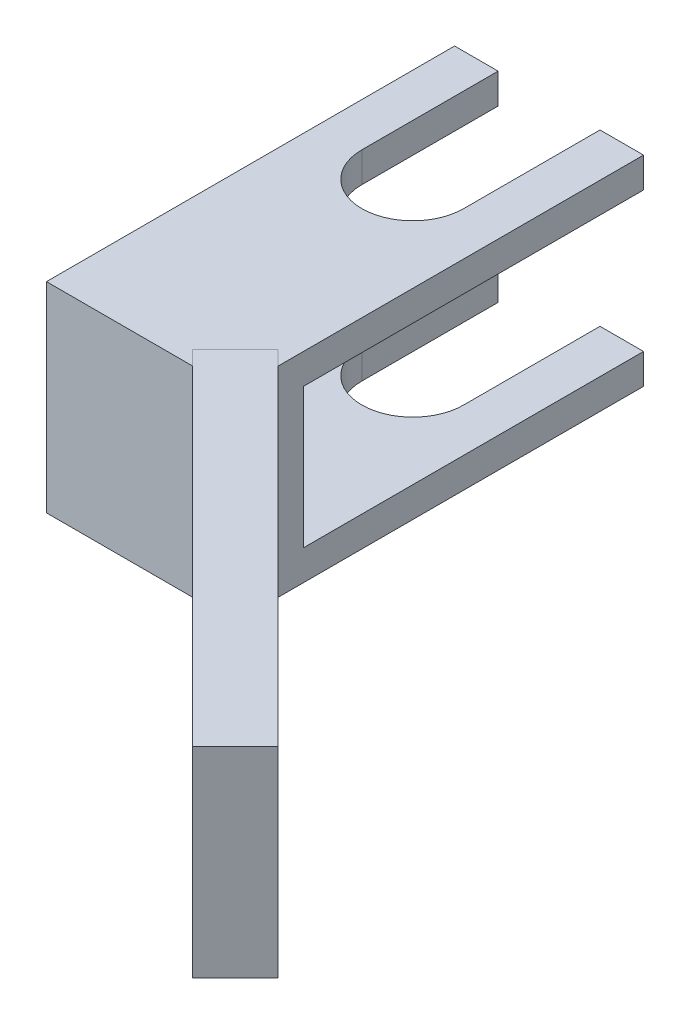
SolidWorks part; units mm, degrees
ref_plane "Front Plane" through (0, 0, 0) normal (0, 0, 1) x (1, 0, 0)
ref_plane "Top Plane" through (0, 0, 0) normal (0, 1, 0) x (1, 0, 0)
ref_plane "Right Plane" through (0, 0, 0) normal (1, 0, 0) x (0, 0, -1)
sketch "Sketch1" plane through (0, 0, 0) normal (0, 1, 0) x (1, 0, 0)
  line L1 (0, 0) -> (50, 0)
  line L2 (0, 0) -> (0, 100)
  line L3 (0, 100) -> (50, 100)
  line L4 (50, 0) -> (50, 100)
  dimension "D1" = 50
  dimension "D2" = 100
extrude "Boss-Extrude1" add sketch "Sketch1" along normal blind 8
sketch "Sketch2" plane through (0, 8, 0) normal (0, 1, 0) x (1, 0, 0)
  line L0 (24.9969, 63.9389) -> (25, 100) construction
  line L1 (50, 100) -> (0, 100) construction
  line L2 (11.5173, 63.94) -> (11.5204, 100.0012)
  line L3 (38.4764, 63.9377) -> (38.4796, 99.9988)
  arc A0 (11.5173, 63.94) -> (38.4764, 63.9377) centre (24.9969, 63.9389) ccw
  arc A1 (38.4796, 99.9988) -> (11.5204, 100.0012) centre (25, 100) ccw
  point P4 (24.9984, 81.9694)
  point P9 (24.9969, 63.9389)
extrude "Cut-Extrude1" cut sketch "Sketch2" against normal blind 8
pattern_linear "LPattern1" count 2 spacing 45 along (0, 1, 0) of "Boss-Extrude1"
sketch "Sketch3" plane through (0, 0, 0) normal (0, 0, 1) x (1, 0, 0)
  line L1 (0, 0) -> (50, 0)
  line L2 (0, 0) -> (0, 53)
  line L3 (0, 53) -> (50, 53)
  line L4 (50, 0) -> (50, 53)
extrude "Boss-Extrude2" add sketch "Sketch3" along normal blind 8 and the other way blind 10
ref_plane "Angled Plane" through (21, 0, -21) normal (0.7071, 0, -0.7071) x (-0.7071, 0, -0.7071)
sketch "Sketch4" plane through (21, 0, -21) normal (0.7071, 0, -0.7071) x (-0.7071, 0, -0.7071)
  line L1 (-27.701, 0) -> (-156.3964, 0)
  line L2 (-27.701, 0) -> (-27.701, 53)
  line L3 (-27.701, 53) -> (-156.3964, 53)
  line L4 (-156.3964, 0) -> (-156.3964, 53)
  point P5 (0, 0)
  point P6 (0, 0)
  point P7 (0, 0)
  point P8 (0, 0)
  point P9 (0, 0)
  point P10 (-36.4741, 0)
  point P11 (0, 0)
  point P12 (0, 0)
extrude "Boss-Extrude3" add sketch "Sketch4" along normal blind 8 and the other way blind 8 separate body
